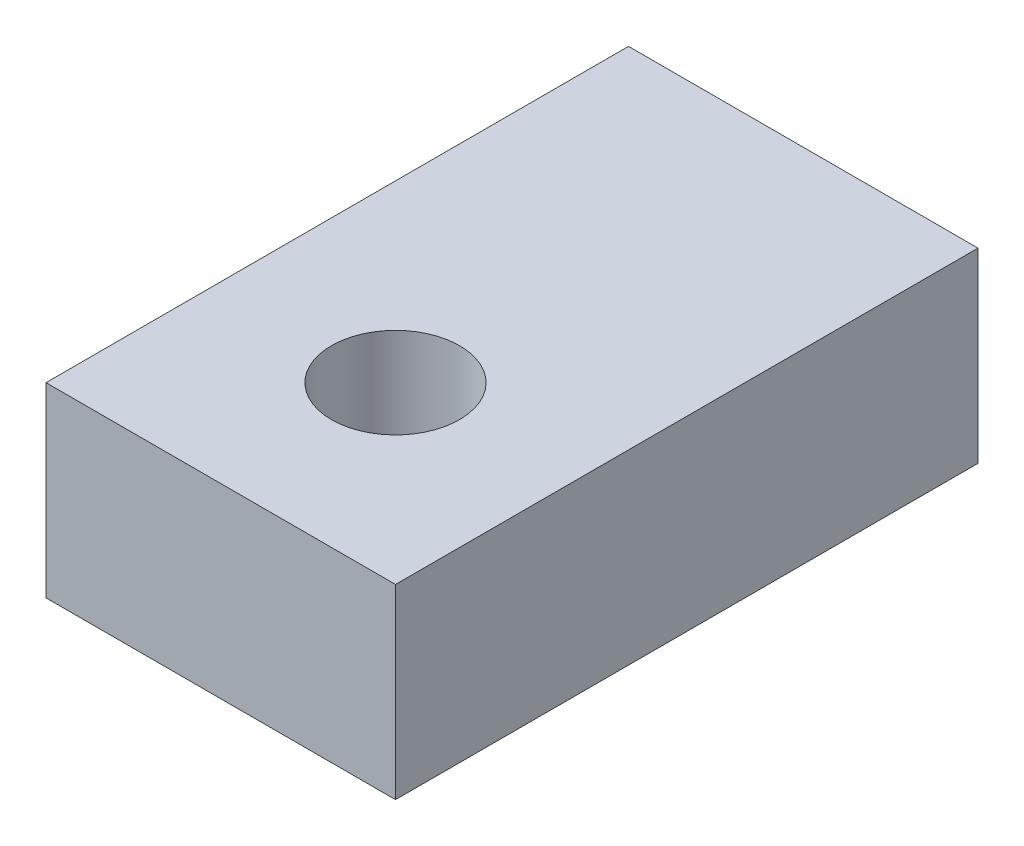
SolidWorks part; units mm, degrees
material "可锻铸铁"
ref_plane "前视基准面" through (0, 0, 0) normal (0, 0, 1) x (1, 0, 0)
ref_plane "上视基准面" through (0, 0, 0) normal (0, 1, 0) x (1, 0, 0)
ref_plane "右视基准面" through (0, 0, 0) normal (1, 0, 0) x (0, 0, -1)
sketch "草图1" plane through (0, 0, 0) normal (0, 1, 0) x (1, 0, 0)
  line L1 (-30, 0) -> (30, 0)
  line L2 (-30, 0) -> (-30, -100)
  line L3 (-30, -100) -> (30, -100)
  line L4 (30, 0) -> (30, -100)
  dimension "D1" = 60
  dimension "D2" = 100
extrude "拉伸1" add sketch "草图1" along normal blind 32
sketch "草图4" plane through (0, 32, 0) normal (0, 1, 0) x (1, 0, 0)
  line L1 (-30, -100) -> (30, -100) construction
  circle A0 centre (0, -70) radius 11
  dimension "D1" = 22
  dimension "D2" = 30
extrude "拉伸3" cut sketch "草图4" against normal through all
